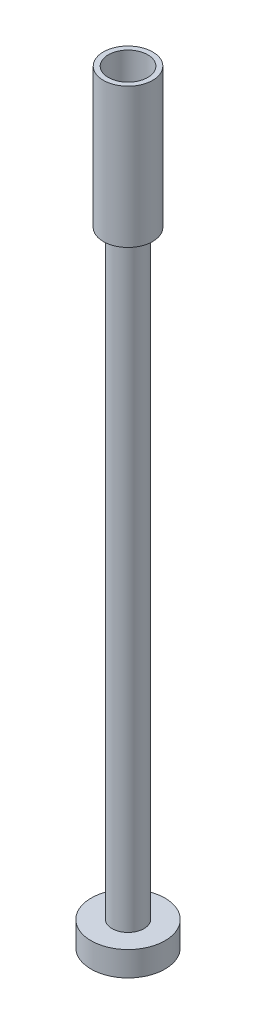
SolidWorks part; units mm, degrees
ref_plane "Front Plane" through (0, 0, 0) normal (0, 0, 1) x (1, 0, 0)
ref_plane "Top Plane" through (0, 0, 0) normal (0, 1, 0) x (1, 0, 0)
ref_plane "Right Plane" through (0, 0, 0) normal (1, 0, 0) x (0, 0, -1)
sketch "Sketch1" plane through (0, 0, 0) normal (0, 1, 0) x (1, 0, 0)
  circle A0 centre (-5.5632, -0.4351) radius 0.8255
  dimension "D1" = 1.651
extrude "Boss-Extrude1" add sketch "Sketch1" along normal blind 38.1
sketch "Sketch3" plane through (0, 0, 0) normal (0, -1, 0) x (1, 0, 0)
  circle A0 centre (-5.5632, 0.4351) radius 1.905
  dimension "D1" = 3.81
extrude "Boss-Extrude2" add sketch "Sketch3" along normal blind 1.27
sketch "Sketch6" plane through (0, 38.1, 0) normal (0, 1, 0) x (1, 0, 0)
  circle A0 centre (-5.5632, -0.4351) radius 1.27
  dimension "D1" = 2.54
extrude "Boss-Extrude5" add sketch "Sketch6" against normal blind 7.2006
sketch "Sketch8" plane through (0, 38.1, 0) normal (0, 1, 0) x (1, 0, 0)
  circle A0 centre (-5.5632, -0.4351) radius 1.016
  dimension "D1" = 2.032
extrude "Cut-Extrude2" cut sketch "Sketch8" against normal blind 2.032
ref_plane "Plane1" through (-6.8332, 0, 0) normal (-1, 0, 0) x (0, 0, 1)
sketch "Sketch9" plane through (-6.8332, 0, 0) normal (-1, 0, 0) x (0, 0, 1)
  line L2 (0, 31.8788) -> (0.4047, 31.8788)
  line L3 (0, 31.8788) -> (0, 32.8948)
  line L4 (0, 32.8948) -> (0.4047, 32.8948)
  line L5 (0.4047, 31.8788) -> (0.4047, 32.8948)
  dimension "D1" = 0.4047
  dimension "D2" = 1.016
extrude "Cut-Extrude3" cut sketch "Sketch9" against normal blind 0.762
